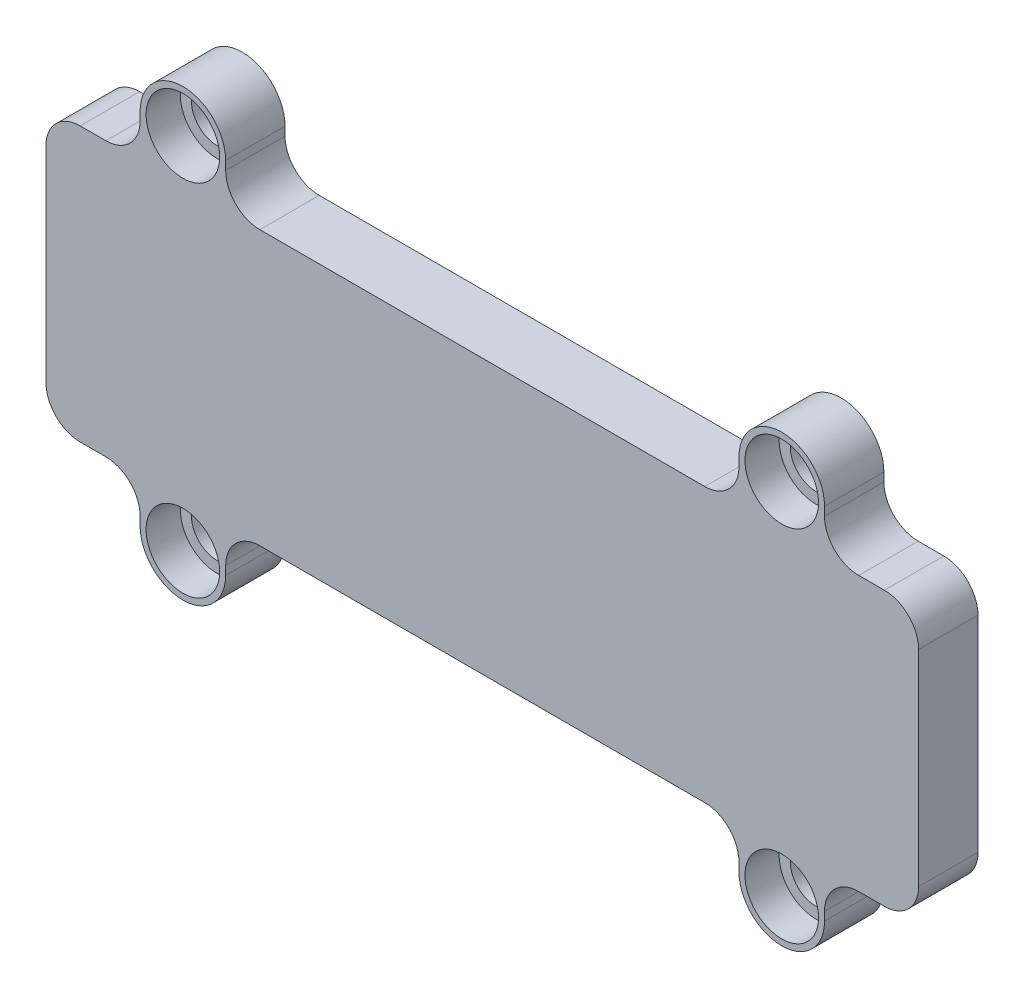
SolidWorks part; units mm, degrees
ref_plane "前视基准面" through (0, 0, 0) normal (0, 0, 1) x (1, 0, 0)
ref_plane "上视基准面" through (0, 0, 0) normal (0, 1, 0) x (1, 0, 0)
ref_plane "右视基准面" through (0, 0, 0) normal (1, 0, 0) x (0, 0, -1)
sketch "草图1" plane through (0, 0, 0) normal (0, 0, 1) x (1, 0, 0)
  line L0 (17.5, 10.5) -> (-17.5, 10.5) construction
  line L1 (-25.5, -8) -> (-20, -8)
  line L2 (-25.5, -8) -> (-25.5, 8)
  line L3 (-25.5, 8) -> (-20, 8)
  line L4 (25.5, -8) -> (25.5, 8)
  line L5 (-25.5, -8) -> (25.5, 8) construction
  line L6 (-25.5, 8) -> (25.5, -8) construction
  line L7 (-17.5, 10.5) -> (-17.5, -10.5) construction
  line L8 (-17.5, -10.5) -> (17.5, -10.5) construction
  line L9 (17.5, -10.5) -> (17.5, 10.5) construction
  line L10 (-20, 10.5) -> (-20, 8)
  line L11 (-15, 10.5) -> (-15, 8)
  line L12 (15, 10.5) -> (15, 8)
  line L13 (20, 10.5) -> (20, 8)
  line L14 (15, -10.5) -> (15, -8)
  line L15 (20, -10.5) -> (20, -8)
  line L16 (-20, -10.5) -> (-20, -8)
  line L17 (-15, -10.5) -> (-15, -8)
  line L18 (-15, 8) -> (15, 8)
  line L19 (20, 8) -> (25.5, 8)
  line L20 (20, -8) -> (25.5, -8)
  line L21 (-15, -8) -> (15, -8)
  arc A0 (-15, 10.5) -> (-20, 10.5) centre (-17.5, 10.5) ccw
  arc A1 (-20, -10.5) -> (-15, -10.5) centre (-17.5, -10.5) ccw
  arc A2 (20, 10.5) -> (15, 10.5) centre (17.5, 10.5) ccw
  arc A3 (15, -10.5) -> (20, -10.5) centre (17.5, -10.5) ccw
  point P0 (0, 0)
  point P27 (-19.5, -8)
  point P28 (-15.5, -8)
  dimension "D7" = 5
  dimension "D8" = 5
  dimension "D9" = 5
  dimension "D10" = 5
  dimension "D1" = 16
  dimension "D2" = 51
  dimension "D3" = 8
  dimension "D4" = 35
  dimension "D5" = 2.5
  dimension "D6" = 2.5
extrude "凸台-拉伸1" add sketch "草图1" along normal blind 3.47
fillet "圆角1" radius 2 12 edges at (20, -8, 1.735) (15, -8, 1.735) (-15, -8, 1.735) (-20, -8, 1.735) (-20, 8, 1.735) (15, 8, 1.735) (20, 8, 1.735) (-15, 8, 1.735) (25.5, -8, 1.735) (25.5, 8, 1.735) (-25.5, -8, 1.735) (-25.5, 8, 1.735)
hole_wizard "大小mm 暗销孔1" positions "草图3" profile "草图4" hole size "Ø3.0" standard "GB" end condition through all
sketch "草图3" plane through (0, 0, 3.47) normal (0, 0, 1) x (1, 0, 0)
  point P0 (-17.5, 10.5)
  point P3 (-17.5, -10.5)
  point P6 (17.5, -10.5)
  point P9 (17.5, 10.5)
sketch "草图4" plane through (-17.5, 10.5, 3.47) normal (1, 0, 0) x (0, -1, 0)
  line L0 (0, 0) -> (0, 3.47)
  line L1 (0, 3.47) -> (1.5, 3.47)
  line L2 (1.5, 3.47) -> (1.5, 0.025)
  line L3 (1.5, 0.025) -> (1.525, 0)
  line L5 (1.525, 0) -> (0, 0)
  line L6 (-1.5, 0.025) -> (-1.525, 0) construction
  line L11 (0, -6.35) -> (0, 107.95) construction
  dimension "通孔孔直径" = 3
  dimension "通孔孔深度" = 3.47
  dimension "近端锥形沉头孔直径" = 3.05
  dimension "近端锥形沉头孔角度" = 90
sketch "草图5" plane through (0, 0, 3.47) normal (0, 0, 1) x (1, 0, 0)
  circle A0 centre (-17.5, 10.5) radius 2.15
  circle A1 centre (17.5, 10.5) radius 2.15
  circle A2 centre (-17.5, -10.5) radius 2.15
  circle A3 centre (17.5, -10.5) radius 2.15
  dimension "D1" = 4.3
  dimension "D2" = 4.3
  dimension "D3" = 4.3
  dimension "D4" = 4.3
extrude "切除-拉伸1" cut sketch "草图5" against normal blind 2
